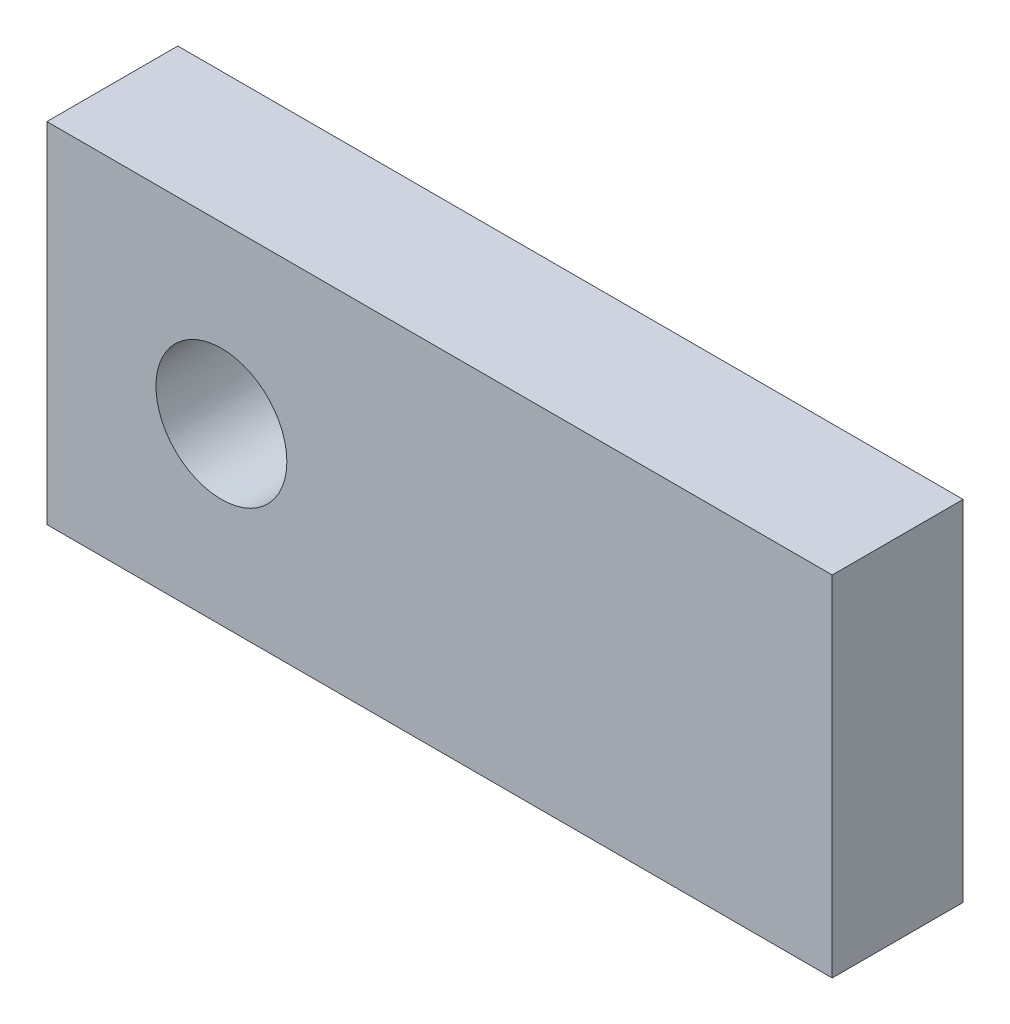
SolidWorks part; units mm, degrees
ref_plane "Спереди" through (0, 0, 0) normal (0, 0, 1) x (1, 0, 0)
ref_plane "Сверху" through (0, 0, 0) normal (0, 1, 0) x (1, 0, 0)
ref_plane "Справа" through (0, 0, 0) normal (1, 0, 0) x (0, 0, -1)
other "Configuration Table"
sketch "Эскиз1" plane through (0, 0, 0) normal (0, 0, 1) x (1, 0, 0)
  line L0 (9, 8) -> (9, 0) construction
  line L1 (0, 0) -> (18, 0)
  line L2 (0, 0) -> (0, 8)
  line L3 (0, 8) -> (18, 8)
  line L4 (18, 0) -> (18, 8)
  line L5 (0, 4) -> (18, 4) construction
  dimension "D1" = 18
  dimension "D2" = 8
extrude "Бобышка-Вытянуть1" add sketch "Эскиз1" along normal blind 3
sketch "Эскиз2" plane through (0, 0, 3) normal (0, 0, 1) x (1, 0, 0)
  line L0 (0, 0) -> (18, 0) construction
  line L1 (0, 8) -> (0, 0) construction
  circle A0 centre (4, 4) radius 1.5
  dimension "D1" = 3
  dimension "D2" = 4
  dimension "D3" = 4
extrude "Вырез-Вытянуть1" cut sketch "Эскиз2" against normal through all
